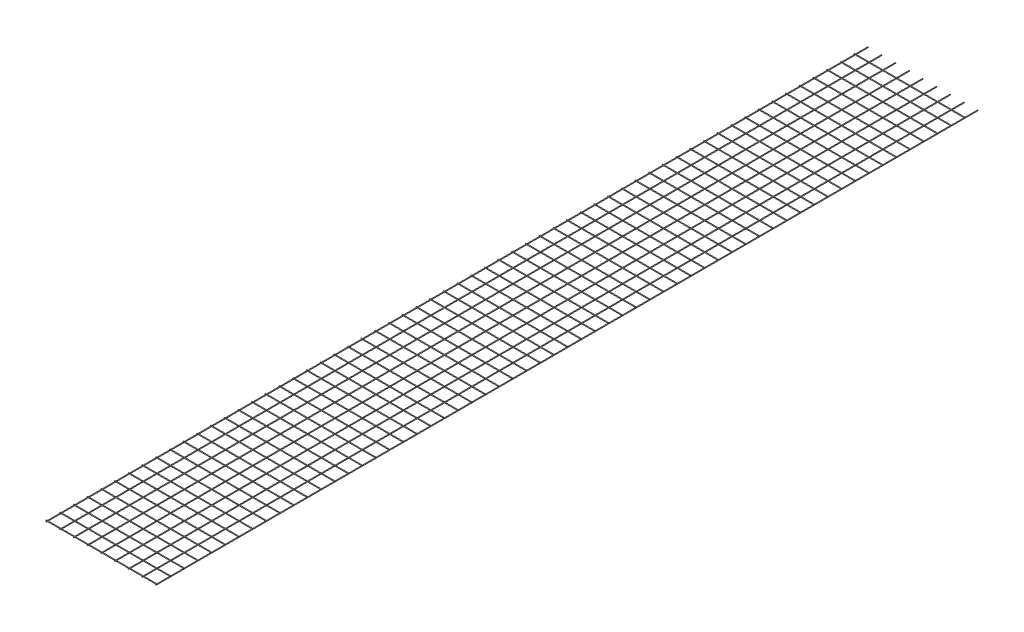
SolidWorks part; units mm, degrees
ref_plane "Front Plane" through (0, 0, 0) normal (0, 0, 1) x (1, 0, 0)
ref_plane "Top Plane" through (0, 0, 0) normal (0, 1, 0) x (1, 0, 0)
ref_plane "Right Plane" through (0, 0, 0) normal (1, 0, 0) x (0, 0, -1)
sketch "Sketch1" plane through (0, 0, 0) normal (0, 0, 1) x (1, 0, 0)
  line L0 (55, 0) -> (-55, 0) construction
  circle A0 centre (-64.4542, 0) radius 2.5
  circle A1 centre (35.5458, 0) radius 2.5
  circle A2 centre (135.5458, 0) radius 2.5
  circle A3 centre (235.5458, 0) radius 2.5
  circle A4 centre (335.5458, 0) radius 2.5
  circle A5 centre (435.5458, 0) radius 2.5
  circle A6 centre (535.5458, 0) radius 2.5
  circle A7 centre (635.5458, 0) radius 2.5
  circle A8 centre (735.5458, 0) radius 2.5
  circle A10 centre (835.5458, 0) radius 2.5 [skipped]
  dimension "D1" = 10
extrude "Boss-Extrude1" add sketch "Sketch1" along normal blind 6000
ref_plane "Plane1" through (738.0458, 0, 0) normal (1, 0, 0) x (0, 0, -1)
sketch "Sketch2" plane through (738.0458, 0, 0) normal (1, 0, 0) x (0, 0, -1)
  circle A1 centre (-5997.5, 5) radius 2.5
  circle A2 centre (-5897.5, 5) radius 2.5
  circle A3 centre (-5797.5, 5) radius 2.5
  circle A4 centre (-5697.5, 5) radius 2.5
  circle A5 centre (-5597.5, 5) radius 2.5
  circle A6 centre (-5497.5, 5) radius 2.5
  circle A7 centre (-5397.5, 5) radius 2.5
  circle A8 centre (-5297.5, 5) radius 2.5
  circle A9 centre (-5197.5, 5) radius 2.5
  circle A10 centre (-5097.5, 5) radius 2.5
  circle A11 centre (-4997.5, 5) radius 2.5
  circle A12 centre (-4897.5, 5) radius 2.5
  circle A13 centre (-4797.5, 5) radius 2.5
  circle A14 centre (-4697.5, 5) radius 2.5
  circle A15 centre (-4597.5, 5) radius 2.5
  circle A16 centre (-4497.5, 5) radius 2.5
  circle A17 centre (-4397.5, 5) radius 2.5
  circle A18 centre (-4297.5, 5) radius 2.5
  circle A19 centre (-4197.5, 5) radius 2.5
  circle A20 centre (-4097.5, 5) radius 2.5
  circle A21 centre (-3997.5, 5) radius 2.5
  circle A22 centre (-3897.5, 5) radius 2.5
  circle A23 centre (-3797.5, 5) radius 2.5
  circle A24 centre (-3697.5, 5) radius 2.5
  circle A25 centre (-3597.5, 5) radius 2.5
  circle A26 centre (-3497.5, 5) radius 2.5
  circle A27 centre (-3397.5, 5) radius 2.5
  circle A28 centre (-3297.5, 5) radius 2.5
  circle A29 centre (-3197.5, 5) radius 2.5
  circle A30 centre (-3097.5, 5) radius 2.5
  circle A31 centre (-2997.5, 5) radius 2.5
  circle A32 centre (-2897.5, 5) radius 2.5
  circle A33 centre (-2797.5, 5) radius 2.5
  circle A34 centre (-2697.5, 5) radius 2.5
  circle A35 centre (-2597.5, 5) radius 2.5
  circle A36 centre (-2497.5, 5) radius 2.5
  circle A37 centre (-2397.5, 5) radius 2.5
  circle A38 centre (-2297.5, 5) radius 2.5
  circle A39 centre (-2197.5, 5) radius 2.5
  circle A40 centre (-2097.5, 5) radius 2.5
  circle A41 centre (-1997.5, 5) radius 2.5
  circle A42 centre (-1897.5, 5) radius 2.5
  circle A43 centre (-1797.5, 5) radius 2.5
  circle A44 centre (-1697.5, 5) radius 2.5
  circle A45 centre (-1597.5, 5) radius 2.5
  circle A46 centre (-1497.5, 5) radius 2.5
  circle A47 centre (-1397.5, 5) radius 2.5
  circle A48 centre (-1297.5, 5) radius 2.5
  circle A49 centre (-1197.5, 5) radius 2.5
  circle A50 centre (-1097.5, 5) radius 2.5
  circle A51 centre (-997.5, 5) radius 2.5
  circle A52 centre (-897.5, 5) radius 2.5
  circle A53 centre (-797.5, 5) radius 2.5
  circle A54 centre (-697.5, 5) radius 2.5
  circle A55 centre (-597.5, 5) radius 2.5
  circle A56 centre (-497.5, 5) radius 2.5
  circle A57 centre (-397.5, 5) radius 2.5
  circle A58 centre (-297.5, 5) radius 2.5
  circle A59 centre (-197.5, 5) radius 2.5
  circle A60 centre (-97.5, 5) radius 2.5
  dimension "D1" = 60
extrude "Boss-Extrude2" add sketch "Sketch2" against normal blind 805 separate body
